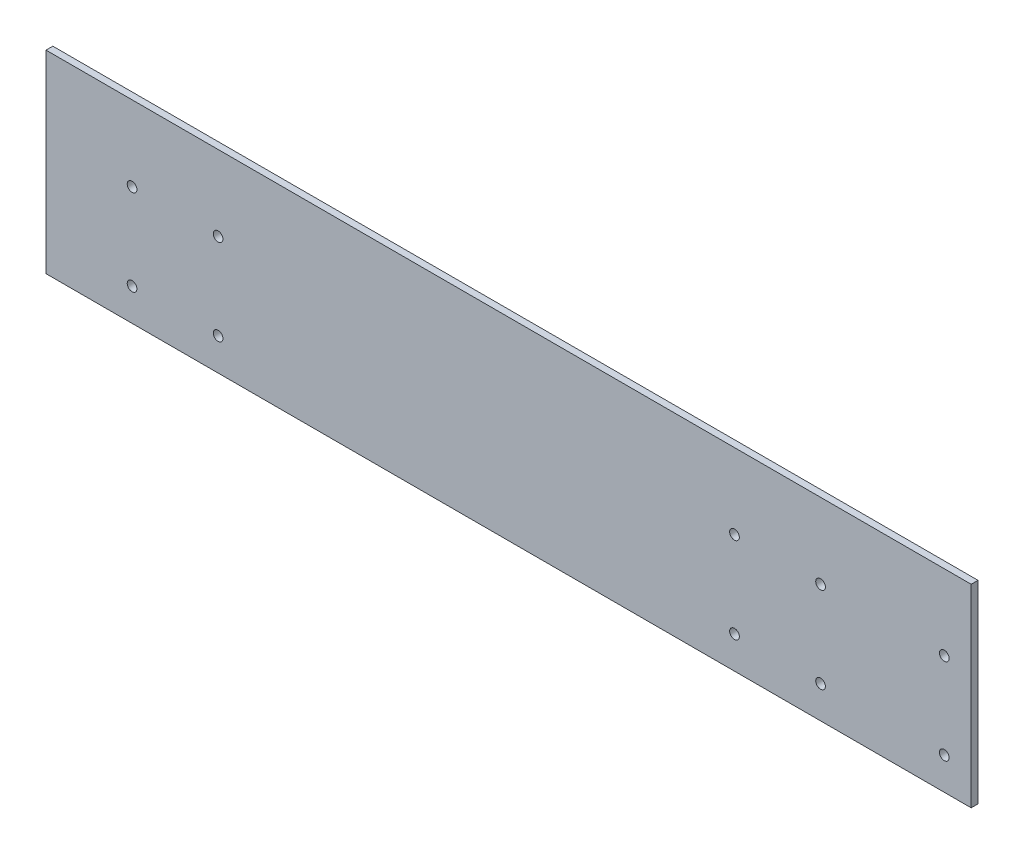
SolidWorks part; units mm, degrees
ref_plane "Front Plane" through (0, 0, 0) normal (0, 0, 1) x (1, 0, 0)
ref_plane "Top Plane" through (0, 0, 0) normal (0, 1, 0) x (1, 0, 0)
ref_plane "Right Plane" through (0, 0, 0) normal (1, 0, 0) x (0, 0, -1)
sketch "Sketch3" plane through (0, 0, 0) normal (0, 0, 1) x (1, 0, 0)
  line L1 (-215, -45) -> (215, -45)
  line L2 (-215, -45) -> (-215, 45)
  line L3 (-215, 45) -> (215, 45)
  line L4 (215, -45) -> (215, 45)
  line L5 (-215, -45) -> (215, 45) construction
  line L6 (-215, 45) -> (215, -45) construction
  point P0 (0, 0)
  dimension "D1" = 430
  dimension "D2" = 90
extrude "Boss-Extrude1" add sketch "Sketch3" along normal blind 3.175
hole_wizard "M4 Clearance Hole1" positions "Sketch4" profile "Sketch5" hole size "M4" standard "ANSI Metric"
sketch "Sketch4" plane through (0, 0, 3.175) normal (0, 0, 1) x (1, 0, 0)
  line L1 (-175, -30) -> (-135, -30)
  line L2 (-175, -30) -> (-175, 10)
  line L3 (-175, 10) -> (-135, 10)
  line L4 (-135, -30) -> (-135, 10)
  line L5 (-175, -30) -> (-135, 10) construction
  line L6 (-175, 10) -> (-135, -30) construction
  line L7 (-215, -45) -> (215, -45) construction
  line L8 (105, -30) -> (145, -30)
  line L9 (105, -30) -> (105, 10)
  line L10 (105, 10) -> (145, 10)
  line L11 (145, -30) -> (145, 10)
  line L12 (105, -30) -> (145, 10) construction
  line L13 (105, 10) -> (145, -30) construction
  line L14 (202.5, 10) -> (202.5, -30)
  line L16 (215, -45) -> (215, 45) construction
  point P2 (-135, 10)
  point P37 (-175, -30)
  point P38 (-175, 10)
  point P39 (-135, -30)
  point P41 (-155, -10)
  point P48 (145, 10)
  point P49 (105, -30)
  point P50 (105, 10)
  point P51 (145, -30)
  point P52 (202.5, 10)
  point P53 (202.5, -30)
  point P71 (125, -10)
  dimension "D1" = 40
  dimension "D2" = 40
  dimension "D3" = 35
  dimension "D4" = 60
  dimension "D6" = 40
  dimension "D7" = 12.5
  dimension "D8" = 90
  dimension "D5" = 2
sketch "Sketch5" plane through (-135, 10, 3.175) normal (1, 0, 0) x (0, -1, 0)
  line L0 (0, 0) -> (0, 11.4519)
  line L1 (0, 11.4519) -> (2.25, 10.1)
  line L2 (2.25, 10.1) -> (2.25, 0)
  line L5 (2.25, 0) -> (0, 0)
  line L10 (0, 11.4519) -> (-2.25, 10.1) construction
  line L11 (0, -6.35) -> (0, 107.95) construction
  dimension "Hole Dia." = 4.5
  dimension "Hole Depth" = 10.1
  dimension "Drill Angle" = 118
